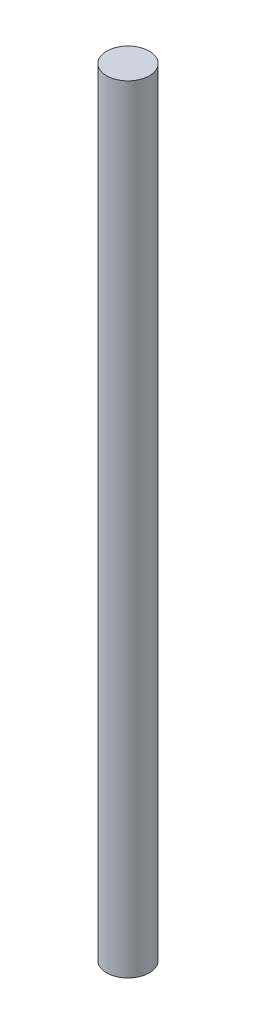
SolidWorks part; units mm, degrees
ref_plane "Front Plane" through (0, 0, 0) normal (0, 0, 1) x (1, 0, 0)
ref_plane "Top Plane" through (0, 0, 0) normal (0, 1, 0) x (1, 0, 0)
ref_plane "Right Plane" through (0, 0, 0) normal (1, 0, 0) x (0, 0, -1)
sketch "Sketch1" plane through (0, 0, 0) normal (0, 1, 0) x (1, 0, 0)
  circle A0 centre (0, 0) radius 2.75
  dimension "D1" = 5.5
extrude "Boss-Extrude1" add sketch "Sketch1" along normal blind 100
